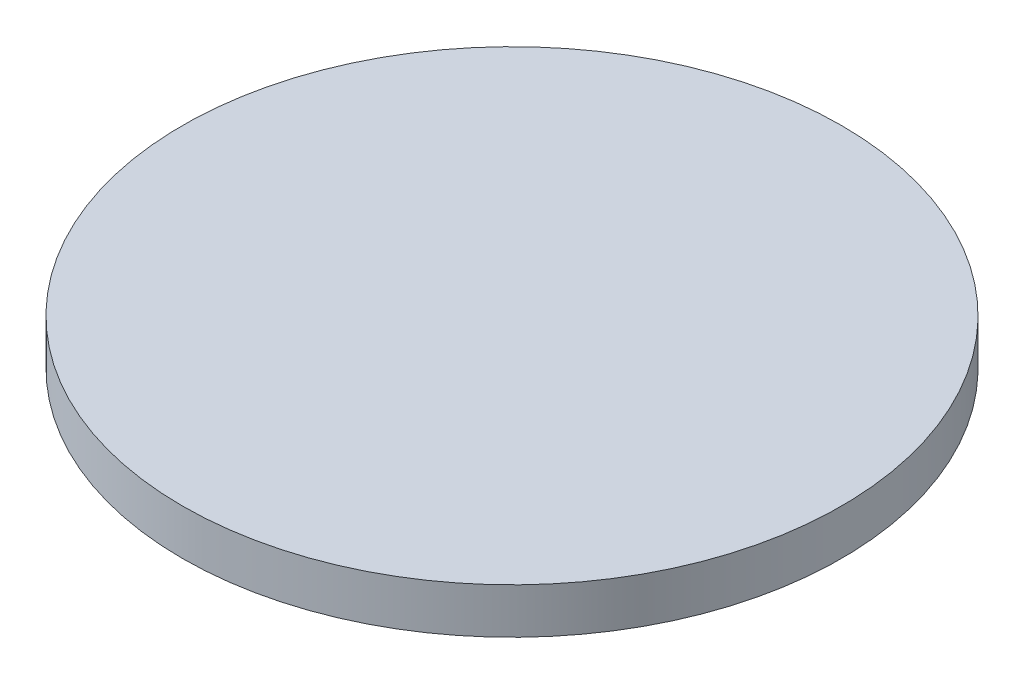
SolidWorks part; units mm, degrees
ref_plane "Front Plane" through (0, 0, 0) normal (0, 0, 1) x (1, 0, 0)
ref_plane "Top Plane" through (0, 0, 0) normal (0, 1, 0) x (1, 0, 0)
ref_plane "Right Plane" through (0, 0, 0) normal (1, 0, 0) x (0, 0, -1)
sketch "Sketch1" plane through (0, 0, 0) normal (0, 1, 0) x (1, 0, 0)
  circle A0 centre (0, 0) radius 217.5
  dimension "D1" = 435
extrude "Boss-Extrude1" add sketch "Sketch1" along normal mid plane 30
